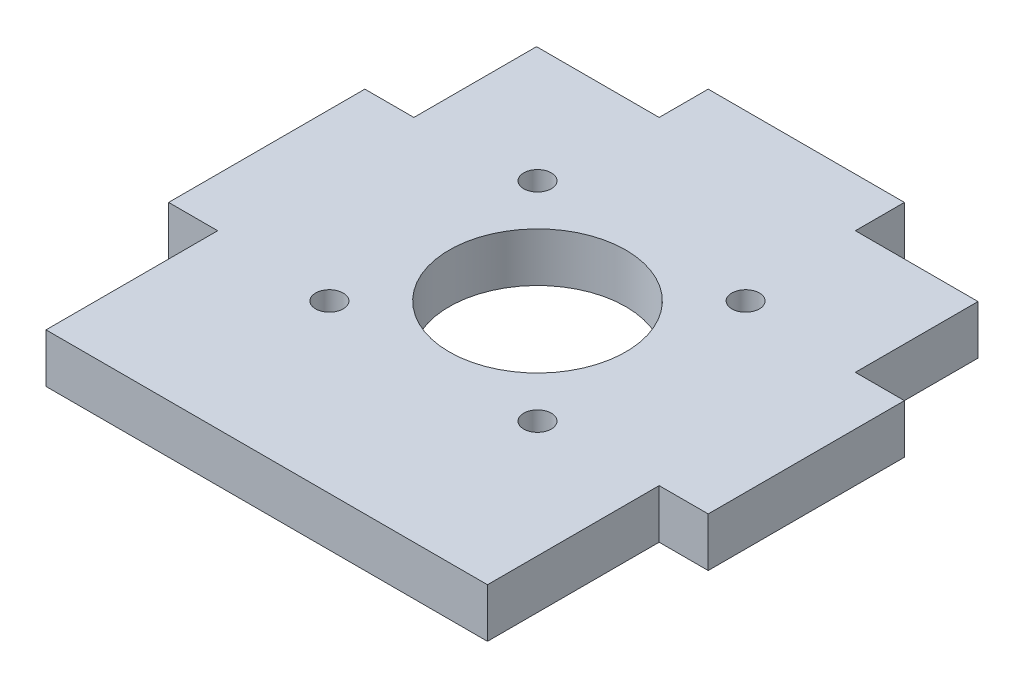
SolidWorks part; units mm, degrees
ref_plane "Front Plane" through (0, 0, 0) normal (0, 0, 1) x (1, 0, 0)
ref_plane "Top Plane" through (0, 0, 0) normal (0, 1, 0) x (1, 0, 0)
ref_plane "Right Plane" through (0, 0, 0) normal (1, 0, 0) x (0, 0, -1)
sketch "Sketch1" plane through (0, 0, 0) normal (0, 1, 0) x (1, 0, 0)
  line L0 (6.35, 47.625) -> (0, 47.625)
  line L1 (0, 0) -> (69.85, 0) construction
  line L2 (0, 0) -> (0, 69.85) construction
  line L3 (0, 69.85) -> (69.85, 69.85) construction
  line L4 (69.85, 0) -> (69.85, 69.85) construction
  line L5 (0, 47.625) -> (0, 22.225)
  line L6 (0, 22.225) -> (6.35, 22.225)
  line L7 (6.35, 22.225) -> (6.35, 0)
  line L8 (6.35, 0) -> (63.5, 0)
  line L9 (63.5, 0) -> (63.5, 22.225)
  line L10 (63.5, 22.225) -> (69.85, 22.225)
  line L11 (69.85, 22.225) -> (69.85, 47.625)
  line L12 (69.85, 47.625) -> (63.5, 47.625)
  line L13 (63.5, 47.625) -> (63.5, 63.5)
  line L14 (63.5, 63.5) -> (47.625, 63.5)
  line L15 (47.625, 63.5) -> (47.625, 69.85)
  line L16 (47.625, 69.85) -> (22.225, 69.85)
  line L17 (22.225, 69.85) -> (22.225, 63.5)
  line L18 (22.225, 63.5) -> (6.35, 63.5)
  line L19 (6.35, 63.5) -> (6.35, 47.625)
  line L20 (34.925, 0) -> (34.925, 63.5) construction
  line L21 (22.225, 63.5) -> (47.625, 63.5) construction
  line L22 (34.925, 35.052) -> (0, 35.052) construction
  line L23 (15.875, 16.002) -> (53.975, 54.102) construction
  line L24 (15.875, 16.002) -> (53.975, 16.002) construction
  line L25 (15.875, 16.002) -> (15.875, 54.102) construction
  line L26 (15.875, 54.102) -> (53.975, 54.102) construction
  line L27 (53.975, 16.002) -> (53.975, 54.102) construction
  line L28 (15.875, 54.102) -> (53.975, 16.002) construction
  circle A0 centre (34.925, 35.052) radius 11.43
  circle A1 centre (34.925, 35.052) radius 19.05 construction
  circle A2 centre (21.4546, 48.5224) radius 1.7859
  circle A3 centre (48.3954, 48.5224) radius 1.7859
  circle A4 centre (48.3954, 21.5816) radius 1.7859
  circle A5 centre (21.4546, 21.5816) radius 1.7859
  point P23 (21.4546, 48.5224)
  point P32 (48.3954, 48.5224)
  point P33 (48.3954, 21.5816)
  point P34 (21.4546, 21.5816)
  dimension "D10" = 22.86
  dimension "D11" = 3.5719
  dimension "D12" = 3.5719
  dimension "D13" = 3.5719
  dimension "D14" = 3.5719
  dimension "D1" = 6.35
  dimension "D2" = 6.35
  dimension "D3" = 6.35
  dimension "D4" = 25.4
  dimension "D5" = 25.4
  dimension "D6" = 69.85
  dimension "D7" = 69.85
  dimension "D8" = 38.1
  dimension "D9" = 38.1
  dimension "D15" = 22.225
  dimension "D16" = 35.052
extrude "Extrude1" add sketch "Sketch1" along normal blind 6.35
